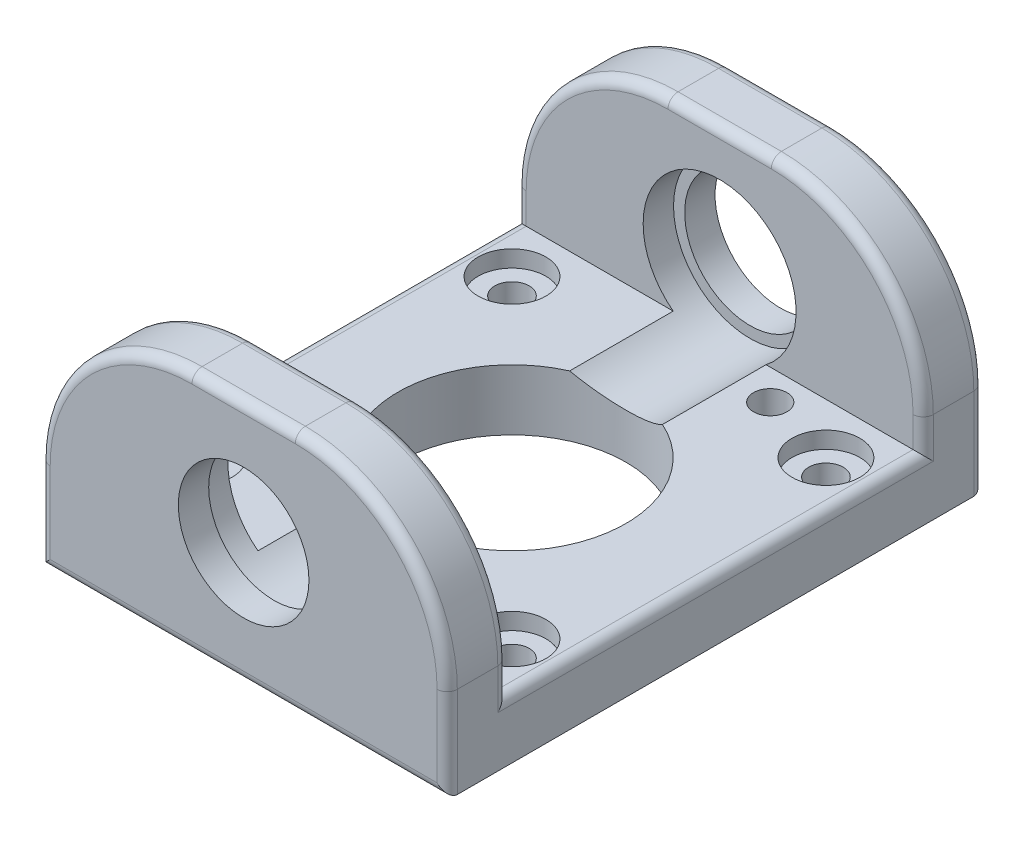
SolidWorks part; units mm, degrees
ref_plane "Front Plane" through (0, 0, 0) normal (0, 0, 1) x (1, 0, 0)
ref_plane "Top Plane" through (0, 0, 0) normal (0, 1, 0) x (1, 0, 0)
ref_plane "Right Plane" through (0, 0, 0) normal (1, 0, 0) x (0, 0, -1)
sketch "Sketch1" plane through (0, 0, 0) normal (0, 1, 0) x (1, 0, 0)
  line L1 (-20.1, 26.5) -> (20.1, 26.5)
  line L2 (-20.1, 26.5) -> (-20.1, -26.5)
  line L3 (-20.1, -26.5) -> (20.1, -26.5)
  line L4 (20.1, 26.5) -> (20.1, -26.5)
  line L5 (-20.1, 26.5) -> (20.1, -26.5) construction
  line L6 (-20.1, -26.5) -> (20.1, 26.5) construction
  circle A0 centre (0, 0) radius 11.25
  dimension "D1" = 22.5
  dimension "D2" = 53
  dimension "D3" = 40.2
extrude "Boss-Extrude1" add sketch "Sketch1" against normal blind 6
sketch "Sketch2" plane through (0, 0, 0) normal (0, 1, 0) x (1, 0, 0)
  line L1 (-15.5, 15.5) -> (15.5, 15.5) construction
  line L2 (-15.5, 15.5) -> (-15.5, -15.5) construction
  line L3 (-15.5, -15.5) -> (15.5, -15.5) construction
  line L4 (15.5, 15.5) -> (15.5, -15.5) construction
  line L5 (-15.5, 15.5) -> (15.5, -15.5) construction
  line L6 (-15.5, -15.5) -> (15.5, 15.5) construction
  circle A0 centre (0, 0) radius 11.25 construction
  point P0 (0, 0)
  dimension "D1" = 31
hole_wizard "CBORE for M3 SBHCS1" positions "Sketch4" profile "Sketch3" counterbore size "M3" standard "ANSI Metric" end condition through all
sketch "Sketch4" plane through (0, 0, 0) normal (0, 1, 0) x (1, 0, 0)
  point P0 (-15.5, 15.5)
  point P3 (15.5, 15.5)
  point P6 (15.5, -15.5)
  point P9 (-15.5, -15.5)
sketch "Sketch3" plane through (-15.5, 0, -15.5) normal (1, 0, 0) x (0, 0, 1)
  line L0 (0, 0) -> (0, 6)
  line L1 (0, 6) -> (1.7, 6)
  line L3 (1.7, 6) -> (1.7, 1.65)
  line L4 (1.7, 1.65) -> (3.35, 1.65)
  line L5 (3.35, 1.65) -> (3.35, 0)
  line L7 (3.35, 0) -> (0, 0)
  line L11 (0, -6.35) -> (0, 107.95) construction
  dimension "Thru Hole Dia." = 3.4
  dimension "Thru Hole Depth" = 6
  dimension "C'Bore Dia." = 6.7
  dimension "C'Bore Depth" = 1.65
sketch "Sketch5" plane through (0, 0, 0) normal (0, 1, 0) x (1, 0, 0)
  line L0 (-20.1, -26.5) -> (20.1, -26.5) construction
  line L1 (-20.1, -20.5) -> (20.1, -20.5)
  line L2 (-20.1, -20.5) -> (-20.1, -26.5)
  line L3 (-20.1, -26.5) -> (20.1, -26.5)
  line L4 (20.1, -20.5) -> (20.1, -26.5)
  line L7 (20.1, 26.5) -> (20.1, -26.5) construction
  line L10 (-20.1, 26.5) -> (-20.1, -26.5) construction
  dimension "D1" = 6
extrude "Boss-Extrude2" add sketch "Sketch5" along normal blind 18
sketch "Sketch6" plane through (0, 0, 26.5) normal (0, 0, 1) x (1, 0, 0)
  line L0 (0, 18) -> (0, 0) construction
  line L1 (-20.1, 18) -> (20.1, 18) construction
  line L2 (-20.1, 6) -> (20.1, 6) construction
  line L3 (-20.1, 18) -> (-20.1, -6) construction
  line L4 (20.1, 18) -> (20.1, -6) construction
  circle A0 centre (0, 6) radius 6.45
  dimension "D1" = 12.9
extrude "Cut-Extrude1" cut sketch "Sketch6" against normal up to next
fillet "Fillet3" radius 15 2 edges at (20.1, 18, 23.5) (-20.1, 18, 23.5)
sketch "Sketch8" plane through (0, 0, 20.5) normal (0, 0, -1) x (-1, 0, 0)
  circle A0 centre (0, 6) radius 7.55
  circle A1 centre (0, 6) radius 6.45 construction
  dimension "D1" = 15.1
extrude "Cut-Extrude3" cut sketch "Sketch8" against normal blind 3 and the other way up to next
mirror "Mirror1" about plane through (0, 0, 0) normal (0, 0, 1) of "Cut-Extrude3", "Boss-Extrude2", "Cut-Extrude1", "Fillet3"
fillet "Fillet4" radius 1 24 edges at (15.7066, 13.6066, 20.5) (0, 18, 20.5) (-15.7066, 13.6066, 20.5) (20.1, 1.5, -20.5) (15.7066, 13.6066, -20.5) (0, 18, -20.5) (-15.7066, 13.6066, -20.5) (20.1, -1.5, -26.5) (15.7066, 13.6066, -26.5) (0, 18, -26.5) (-15.7066, 13.6066, -26.5) (20.1, -1.5, 26.5) (15.7066, 13.6066, 26.5) (0, 18, 26.5) (-15.7066, 13.6066, 26.5) (0, -6, 26.5) (0, -6, -26.5) (-20.1, 1.5, -20.5) (-20.1, -1.5, -26.5) (-20.1, -1.5, 26.5)
hole_wizard "M4x0.7 Tapped Hole1" positions "Sketch9" profile "Sketch10" tap size "M4x0.7" standard "ANSI Metric" end condition through all
sketch "Sketch9" plane through (0, -6, 0) normal (0, -1, 0) x (-1, 0, 0)
  line L0 (-8, 17.5) -> (-8, -17.5) construction
  line L3 (-8, 0) -> (0, 0) construction
  point P0 (-8, 17.5)
  point P2 (-8, -17.5)
  point P14 (-8.2219, 0)
  point P15 (-7.0284, -5.461)
  point P16 (0, 0)
  dimension "D1" = 35
  dimension "D2" = 8
sketch "Sketch10" plane through (8, -6, -17.5) normal (1, 0, 0) x (0, 0, -1)
  line L0 (0, 0) -> (0, 24)
  line L1 (0, 24) -> (1.65, 24)
  line L2 (1.65, 24) -> (1.65, 0)
  line L5 (1.65, 0) -> (0, 0)
  line L11 (0, -6.35) -> (0, 107.95) construction
  dimension "Thru Tap Drill Dia." = 3.3
  dimension "Thru Tap Drill Depth" = 24
cosmetic thread "Hole Thread1" parameters "D2"=4
cosmetic thread "Hole Thread2" parameters "D2"=4
